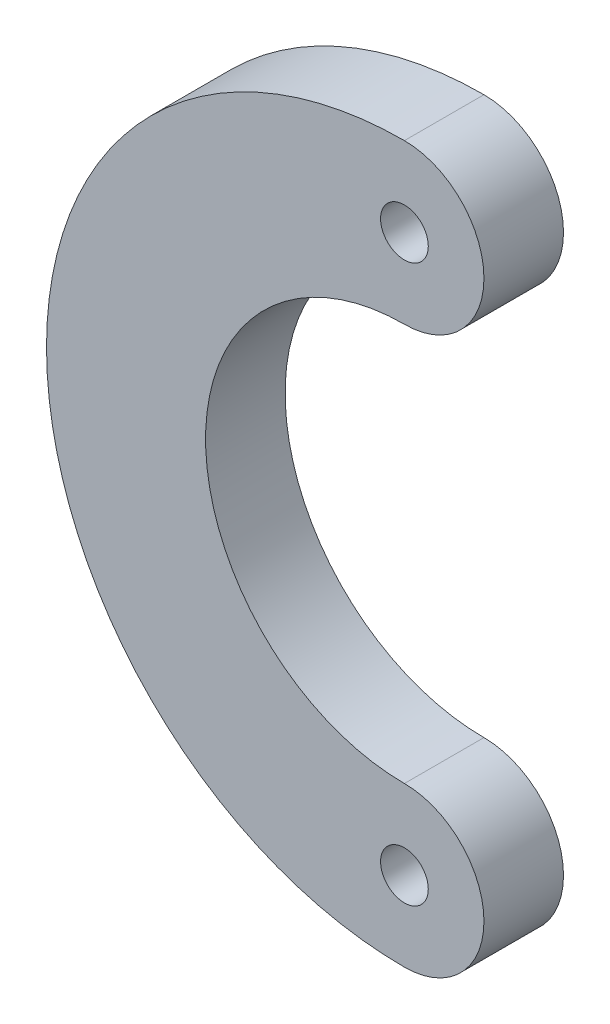
SolidWorks part; units mm, degrees
ref_plane "Front Plane" through (0, 0, 0) normal (0, 0, 1) x (1, 0, 0)
ref_plane "Top Plane" through (0, 0, 0) normal (0, 1, 0) x (1, 0, 0)
ref_plane "Right Plane" through (0, 0, 0) normal (1, 0, 0) x (0, 0, -1)
sketch "Sketch1" plane through (0, 0, 0) normal (0, 0, 1) x (1, 0, 0)
  arc A0 (0, 22.5) -> (0, -22.5) centre (0, 0) ccw
  arc A1 (0, 12.5) -> (0, -12.5) centre (0, 0) ccw
  arc A2 (0, 12.5) -> (0, 22.5) centre (0, 17.5) ccw
  arc A3 (0, -22.5) -> (0, -12.5) centre (0, -17.5) ccw
  dimension "D1" = 10
  dimension "D2" = 35
extrude "Boss-Extrude1" add sketch "Sketch1" along normal blind 5
hole_wizard "Ø3.0mm Dowel Hole1" positions "Sketch2" profile "Sketch3" hole size "Ø3.0" standard "ANSI Metric" end condition through all
sketch "Sketch2" plane through (0, 0, 5) normal (0, 0, 1) x (1, 0, 0)
  arc A0 (0, -22.5) -> (0, -12.5) centre (0, -17.5) ccw construction
  arc A1 (0, 12.5) -> (0, 22.5) centre (0, 17.5) ccw construction
  point P0 (0, 17.5)
  point P2 (0, -17.5)
sketch "Sketch3" plane through (0, 17.5, 5) normal (1, 0, 0) x (0, -1, 0)
  line L0 (0, 0) -> (0, 5)
  line L1 (0, 5) -> (1.5, 5)
  line L2 (1.5, 5) -> (1.5, 0)
  line L5 (1.5, 0) -> (0, 0)
  line L11 (0, -6.35) -> (0, 107.95) construction
  dimension "Thru Hole Dia." = 3
  dimension "Thru Hole Depth" = 5
